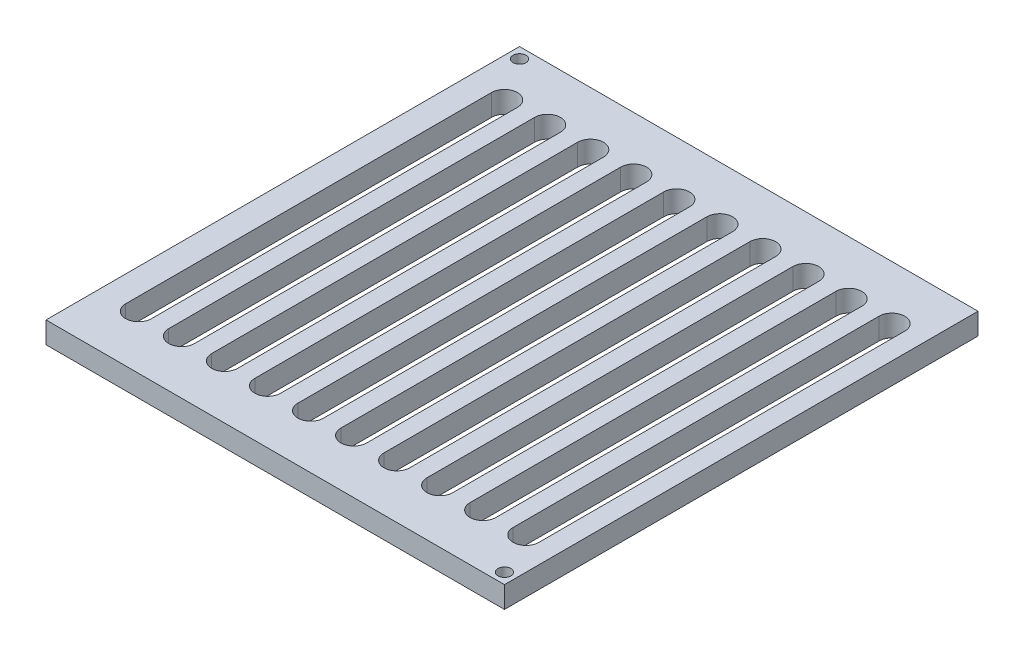
SolidWorks part; units mm, degrees
ref_plane "Front Plane" through (0, 0, 0) normal (0, 0, 1) x (1, 0, 0)
ref_plane "Top Plane" through (0, 0, 0) normal (0, 1, 0) x (1, 0, 0)
ref_plane "Right Plane" through (0, 0, 0) normal (1, 0, 0) x (0, 0, -1)
sketch "Sketch1" plane through (0, 0, 0) normal (0, 1, 0) x (1, 0, 0)
  line L1 (0, 0) -> (54.102, 0)
  line L2 (0, 0) -> (0, 55.88)
  line L3 (0, 55.88) -> (54.102, 55.88)
  line L4 (54.102, 0) -> (54.102, 55.88)
  dimension "D1" = 54.102
  dimension "D2" = 55.88
extrude "Boss-Extrude1" add sketch "Sketch1" along normal blind 2.54
sketch "Sketch2" plane through (0, 2.54, 0) normal (0, 1, 0) x (1, 0, 0)
  line L0 (54.102, 55.88) -> (0, 55.88) construction
  line L1 (0, 55.88) -> (0, 0) construction
  line L2 (54.102, 0) -> (54.102, 55.88) construction
  line L3 (0, 0) -> (54.102, 0) construction
  line L4 (4.572, 49.53) -> (4.572, 6.35) construction
  line L5 (6.096, 49.53) -> (6.096, 6.35)
  line L6 (3.048, 49.53) -> (3.048, 6.35)
  line L7 (9.652, 49.53) -> (9.652, 6.35) construction
  line L8 (11.176, 49.53) -> (11.176, 6.35)
  line L9 (8.128, 49.53) -> (8.128, 6.35)
  line L10 (14.732, 49.53) -> (14.732, 6.35) construction
  line L11 (16.256, 49.53) -> (16.256, 6.35)
  line L12 (13.208, 49.53) -> (13.208, 6.35)
  line L13 (19.812, 49.53) -> (19.812, 6.35) construction
  line L14 (21.336, 49.53) -> (21.336, 6.35)
  line L15 (18.288, 49.53) -> (18.288, 6.35)
  line L16 (24.892, 49.53) -> (24.892, 6.35) construction
  line L17 (26.416, 49.53) -> (26.416, 6.35)
  line L18 (23.368, 49.53) -> (23.368, 6.35)
  line L19 (29.972, 49.53) -> (29.972, 6.35) construction
  line L20 (31.496, 49.53) -> (31.496, 6.35)
  line L21 (28.448, 49.53) -> (28.448, 6.35)
  line L22 (35.052, 49.53) -> (35.052, 6.35) construction
  line L23 (36.576, 49.53) -> (36.576, 6.35)
  line L24 (33.528, 49.53) -> (33.528, 6.35)
  line L25 (40.132, 49.53) -> (40.132, 6.35) construction
  line L26 (41.656, 49.53) -> (41.656, 6.35)
  line L27 (38.608, 49.53) -> (38.608, 6.35)
  line L28 (45.212, 49.53) -> (45.212, 6.35) construction
  line L29 (46.736, 49.53) -> (46.736, 6.35)
  line L30 (43.688, 49.53) -> (43.688, 6.35)
  line L31 (50.292, 49.53) -> (50.292, 6.35) construction
  line L32 (51.816, 49.53) -> (51.816, 6.35)
  line L33 (48.768, 49.53) -> (48.768, 6.35)
  circle A0 centre (1.27, 54.61) radius 0.762
  circle A1 centre (52.832, 1.27) radius 0.762
  arc A2 (6.096, 49.53) -> (3.048, 49.53) centre (4.572, 49.53) ccw
  arc A3 (3.048, 6.35) -> (6.096, 6.35) centre (4.572, 6.35) ccw
  arc A4 (11.176, 49.53) -> (8.128, 49.53) centre (9.652, 49.53) ccw
  arc A5 (8.128, 6.35) -> (11.176, 6.35) centre (9.652, 6.35) ccw
  arc A6 (16.256, 49.53) -> (13.208, 49.53) centre (14.732, 49.53) ccw
  arc A7 (13.208, 6.35) -> (16.256, 6.35) centre (14.732, 6.35) ccw
  arc A8 (21.336, 49.53) -> (18.288, 49.53) centre (19.812, 49.53) ccw
  arc A9 (18.288, 6.35) -> (21.336, 6.35) centre (19.812, 6.35) ccw
  arc A10 (26.416, 49.53) -> (23.368, 49.53) centre (24.892, 49.53) ccw
  arc A11 (23.368, 6.35) -> (26.416, 6.35) centre (24.892, 6.35) ccw
  arc A12 (31.496, 49.53) -> (28.448, 49.53) centre (29.972, 49.53) ccw
  arc A13 (28.448, 6.35) -> (31.496, 6.35) centre (29.972, 6.35) ccw
  arc A14 (36.576, 49.53) -> (33.528, 49.53) centre (35.052, 49.53) ccw
  arc A15 (33.528, 6.35) -> (36.576, 6.35) centre (35.052, 6.35) ccw
  arc A16 (41.656, 49.53) -> (38.608, 49.53) centre (40.132, 49.53) ccw
  arc A17 (38.608, 6.35) -> (41.656, 6.35) centre (40.132, 6.35) ccw
  arc A18 (46.736, 49.53) -> (43.688, 49.53) centre (45.212, 49.53) ccw
  arc A19 (43.688, 6.35) -> (46.736, 6.35) centre (45.212, 6.35) ccw
  arc A20 (51.816, 49.53) -> (48.768, 49.53) centre (50.292, 49.53) ccw
  arc A21 (48.768, 6.35) -> (51.816, 6.35) centre (50.292, 6.35) ccw
  point P14 (4.572, 27.94)
  point P22 (9.652, 27.94)
  point P29 (14.732, 27.94)
  point P36 (19.812, 27.94)
  point P43 (24.892, 27.94)
  point P50 (29.972, 27.94)
  point P57 (35.052, 27.94)
  point P64 (40.132, 27.94)
  point P71 (45.212, 27.94)
  point P77 (50.292, 27.94)
  dimension "D1" = 1.524
  dimension "D2" = 1.524
  dimension "D3" = 1.27
  dimension "D4" = 1.27
  dimension "D5" = 1.27
  dimension "D6" = 1.27
  dimension "D8" = 6.35
  dimension "D10" = 1.524
  dimension "D7" = 43.18
  dimension "D9" = 3.048
  dimension "D12" = 2.032
  dimension "D11" = 10
extrude "Cut-Extrude1" cut sketch "Sketch2" against normal blind 49.276
